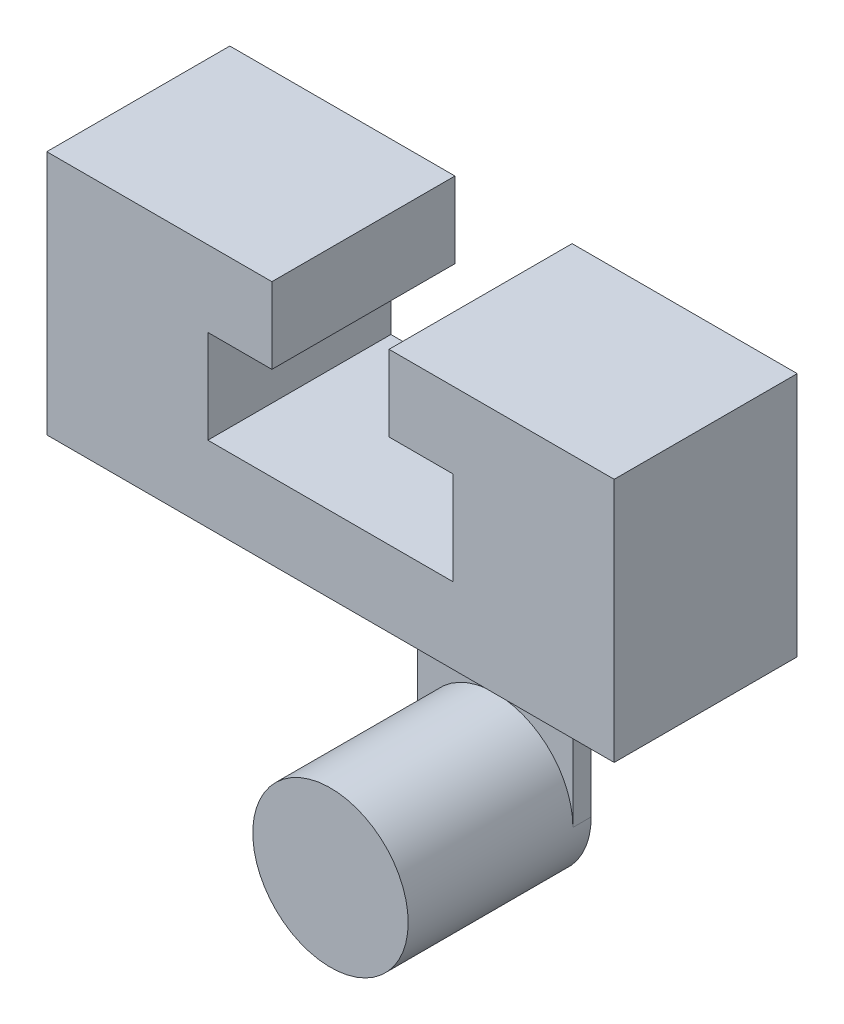
SolidWorks part; units mm, degrees
material "6061-T6 (SS)"
ref_plane "Front Plane" through (0, 0, 0) normal (0, 0, 1) x (1, 0, 0)
ref_plane "Top Plane" through (0, 0, 0) normal (0, 1, 0) x (1, 0, 0)
ref_plane "Right Plane" through (0, 0, 0) normal (1, 0, 0) x (0, 0, -1)
sketch "Sketch4" plane through (0, 0, 0) normal (0, 0, 1) x (1, 0, 0)
  line L0 (39.37, 0) -> (39.37, 34.036) construction
  line L1 (0, 0) -> (28.5877, 0)
  line L2 (0, 0) -> (0, 34.036)
  line L3 (0, 34.036) -> (78.74, 34.036)
  line L4 (78.74, 0) -> (78.74, 34.036)
  line L5 (28.5877, -33.528) -> (28.5877, 0)
  line L6 (22.352, 10.541) -> (56.388, 10.541)
  line L7 (22.352, 10.541) -> (22.352, 23.495)
  line L8 (22.352, 23.495) -> (56.388, 23.495)
  line L9 (56.388, 10.541) -> (56.388, 23.495)
  line L10 (22.352, 10.541) -> (56.388, 23.495) construction
  line L11 (22.352, 23.495) -> (56.388, 10.541) construction
  line L12 (50.1523, -33.528) -> (50.1523, 0)
  line L13 (50.1523, 0) -> (78.74, 0)
  arc A0 (28.5877, -33.528) -> (50.1523, -33.528) centre (39.37, -33.528) ccw
  point P7 (39.37, 17.018)
  dimension "D5" = 21.5646
  dimension "D1" = 34.036
  dimension "D2" = 78.74
  dimension "D3" = 34.036
  dimension "D4" = 12.954
  dimension "D6" = 33.528
extrude "Boss-Extrude3" add sketch "Sketch4" along normal blind 25.4 separate body contours L5 L1 L2 L3 L4 L13 L12 A0
sketch "Sketch5" plane through (0, 0, 25.4) normal (0, 0, 1) x (1, 0, 0)
  line L0 (39.37, 34.036) -> (39.37, 0) construction
  line L1 (0, 34.036) -> (78.74, 34.036) construction
  line L2 (47.498, 23.495) -> (56.388, 23.495)
  line L3 (22.352, 10.541) -> (56.388, 10.541)
  line L4 (22.352, 10.541) -> (22.352, 23.495)
  line L5 (22.352, 23.495) -> (31.242, 23.495)
  line L6 (56.388, 10.541) -> (56.388, 23.495)
  line L7 (22.352, 10.541) -> (56.388, 23.495) construction
  line L8 (22.352, 23.495) -> (56.388, 10.541) construction
  line L10 (31.242, 23.495) -> (31.242, 34.036)
  line L11 (31.242, 34.036) -> (47.498, 34.036)
  line L12 (47.498, 23.495) -> (47.498, 34.036)
  point P5 (39.37, 17.018)
  dimension "D1" = 34.036
  dimension "D2" = 12.954
  dimension "D3" = 8.89
  dimension "D4" = 8.89
extrude "Cut-Extrude2" cut sketch "Sketch5" against normal through all
sketch "Sketch7" plane through (0, 0, 25.4) normal (0, 0, 1) x (1, 0, 0)
  line L1 (28.5877, 0) -> (50.1523, 0)
  line L2 (28.5877, 0) -> (28.5877, -33.528)
  line L4 (50.1523, 0) -> (50.1523, -33.528)
  arc A0 (28.5877, -33.528) -> (50.1523, -33.528) centre (39.37, -33.528) ccw
extrude "Cut-Extrude3" cut sketch "Sketch7" against normal blind 22.86
sketch "Sketch8" plane through (0, 0, 2.54) normal (0, 0, 1) x (1, 0, 0)
  circle A0 centre (39.37, -33.528) radius 10.7823
  dimension "D1" = 21.5646
extrude "Boss-Extrude4" add sketch "Sketch8" along normal blind 22.86
equation "\"F\"= 600"
equation "\"SF\"= 4"
equation "\"YM\"= 10000000"
equation "\"MaxDef\"= 0.005in"
equation "\"Length of Pin\"= 2"
equation "\"YS\"= 40000"
equation "\"Wofphi\"= 1.25"
equation "\"Le\"= 1.5"
equation "\"We\"= 3.1"
equation "\"Hb\"= 0.51"
equation "\"D_A\"= 0.849in"
equation "\"T_B\"= 0.137in"
equation "\"W_C\"= 1.342in"
equation "\"T_D\"= 0.0436in"
equation "\"Wa\"= 1"
equation "\"T_E\"= 1.342in"
equation "\"AllowStress\"= \"YS\" / \"SF\""
